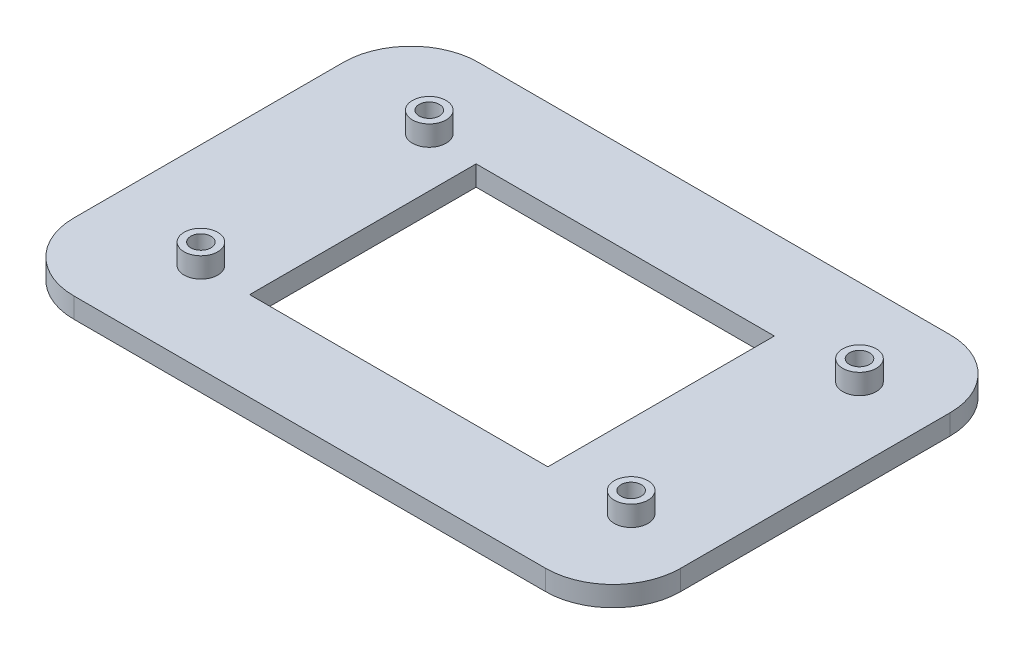
SolidWorks part; units mm, degrees
ref_plane "前基準面" through (0, 0, 0) normal (0, 0, 1) x (1, 0, 0)
ref_plane "上基準面" through (0, 0, 0) normal (0, 1, 0) x (1, 0, 0)
ref_plane "右基準面" through (0, 0, 0) normal (1, 0, 0) x (0, 0, -1)
sketch "草圖1" plane through (0, 0, 0) normal (0, 1, 0) x (1, 0, 0)
  line L1 (-60.8537, 27.6829) -> (29.1463, 27.6829)
  line L2 (-60.8537, 27.6829) -> (-60.8537, -32.3171)
  line L3 (-60.8537, -32.3171) -> (29.1463, -32.3171)
  line L4 (29.1463, 27.6829) -> (29.1463, -32.3171)
  dimension "D1" = 90
  dimension "D2" = 60
extrude "填料-伸長1" add sketch "草圖1" along normal blind 3
sketch "草圖2" plane through (0, 3, 0) normal (0, 1, 0) x (1, 0, 0)
  line L1 (-37.9687, 14.4779) -> (6.2613, 14.4779)
  line L2 (-37.9687, 14.4779) -> (-37.9687, -19.1121)
  line L3 (-37.9687, -19.1121) -> (6.2613, -19.1121)
  line L4 (6.2613, 14.4779) -> (6.2613, -19.1121)
  line L5 (29.1463, 27.6829) -> (-60.8537, 27.6829) construction
  line L7 (-60.8537, 27.6829) -> (-60.8537, -32.3171) construction
  circle A0 centre (-45.3387, 14.8979) radius 1.5
  circle A1 centre (-45.3387, -18.9721) radius 1.5
  circle A2 centre (18.4713, 14.8979) radius 1.5
  circle A3 centre (18.4713, -18.9721) radius 1.5
  point P12 (0, 0)
  point P13 (0, 0)
  point P14 (0, 0)
  dimension "D3" = 3
  dimension "D4" = 3
  dimension "D5" = 3
  dimension "D6" = 3
  dimension "D1" = 44.23
  dimension "D2" = 33.59
  dimension "D7" = 63.81
  dimension "D8" = 63.81
  dimension "D9" = 0
  dimension "D10" = 0
  dimension "D11" = 0
  dimension "D12" = 33.87
  dimension "D13" = 7.37
  dimension "D14" = 0.14
  dimension "D15" = 13.205
  dimension "D16" = 22.885
extrude "除料-伸長1" cut sketch "草圖2" against normal through all
fillet "圓角1" radius 10 4 edges at (29.1463, 1.5, -27.6829) (29.1463, 1.5, 32.3171) (-60.8537, 1.5, 32.3171) (-60.8537, 1.5, -27.6829)
sketch "草圖3" plane through (0, 3, 0) normal (0, 1, 0) x (1, 0, 0)
  circle A0 centre (-45.3387, 14.8979) radius 2.5
  circle A1 centre (-45.3387, -18.9721) radius 2.5
  circle A2 centre (18.4713, -18.9721) radius 2.5
  circle A3 centre (18.4713, 14.8979) radius 2.5
  point P12 (0, 0)
  dimension "D1" = 5
  dimension "D2" = 5
  dimension "D3" = 5
  dimension "D4" = 5
extrude "填料-伸長2" add sketch "草圖3" along normal blind 3
sketch "草圖4" plane through (0, 6, 0) normal (0, 1, 0) x (1, 0, 0)
  circle A0 centre (-45.3387, 14.8979) radius 1.5
  circle A1 centre (-45.3387, -18.9721) radius 1.5
  circle A2 centre (18.4713, 14.8979) radius 1.5
  circle A3 centre (18.4713, -18.9721) radius 1.5
  dimension "D1" = 3
  dimension "D2" = 3
  dimension "D3" = 3
  dimension "D4" = 3
extrude "除料-伸長2" cut sketch "草圖4" against normal through all
